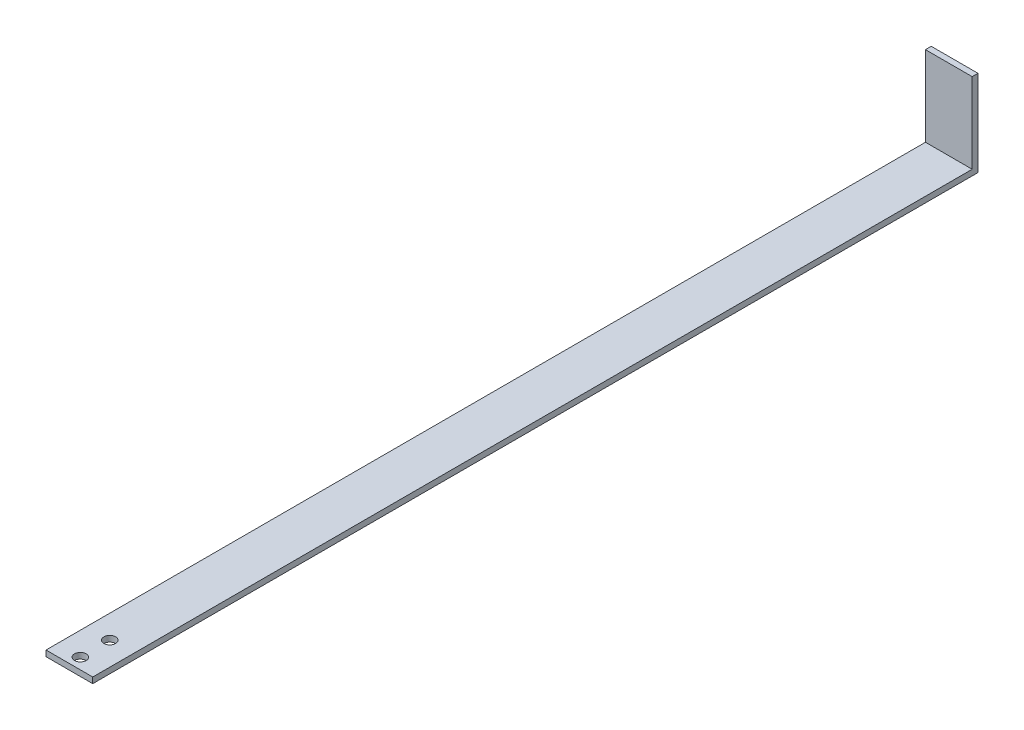
SolidWorks part; units mm, degrees
ref_plane "Alzado" through (0, 0, 0) normal (0, 0, 1) x (1, 0, 0)
ref_plane "Planta" through (0, 0, 0) normal (0, 1, 0) x (1, 0, 0)
ref_plane "Vista lateral" through (0, 0, 0) normal (1, 0, 0) x (0, 0, -1)
sketch "Croquis1" plane through (0, 0, 0) normal (1, 0, 0) x (0, 0, -1)
  line L0 (-6.31, 93.46) -> (0, 93.46)
  line L1 (0, 93.46) -> (0, 0)
  line L2 (0, 0) -> (-962, 0)
  line L3 (-962, 0) -> (-962, 6.31)
  line L4 (-962, 6.31) -> (-6.31, 6.31)
  line L5 (-6.31, 6.31) -> (-6.31, 93.46)
  dimension "D1" = 962
  dimension "D2" = 6.31
  dimension "D3" = 93.46
  dimension "D4" = 6.31
extrude "Saliente-Extruir1" add sketch "Croquis1" along normal blind 50.8
sketch "Croquis4" plane through (0, 0, 0) normal (0, -1, 0) x (-1, 0, 0)
  line L0 (-25.4753, -943.7582) -> (-25.4, -950.1078) construction
  line L1 (-25.4, -950.1078) -> (-25.4957, -943.7585) construction
  line L2 (-25.4027, -911.7578) -> (-25.4, -918.1078) construction
  line L3 (-25.4, -918.1078) -> (-31.75, -918.1078) construction
  circle A0 centre (-25.4, -950.1078) radius 6.35 construction
  circle A1 centre (-25.4, -950.1078) radius 6.35
  circle A2 centre (-25.4, -918.1078) radius 6.35 construction
  circle A3 centre (-25.4, -918.1078) radius 6.35
sketch "Croquis6" plane through (0, 0, 0) normal (0, -1, 0) x (1, 0, 0)
  line L0 (25.4, 950.1078) -> (19.05, 950.1078) construction
  line L1 (25.4, 918.1078) -> (20.9099, 922.5979) construction
  circle A0 centre (25.4, 918.1078) radius 6.35
  circle A1 centre (25.4, 950.1078) radius 6.35
extrude "Cortar-Extruir1" cut sketch "Croquis6" against normal blind 10
